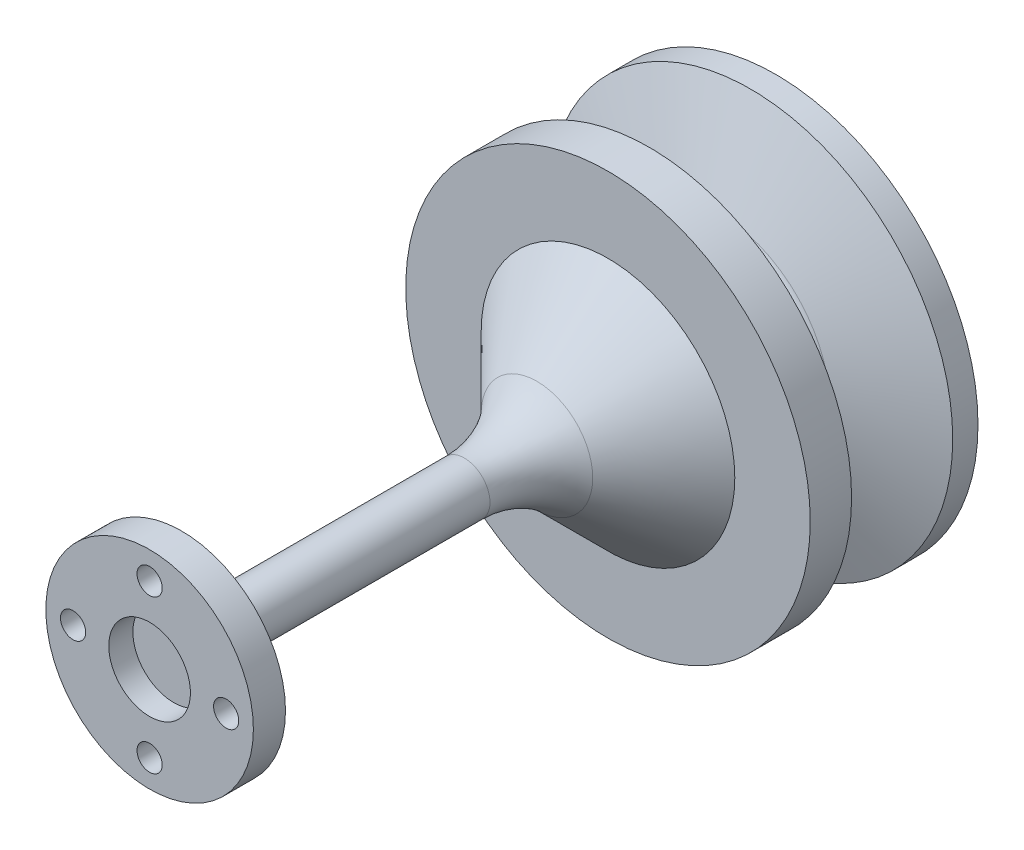
SolidWorks part; units mm, degrees
ref_plane "Plan de face" through (0, 0, 0) normal (0, 0, 1) x (1, 0, 0)
ref_plane "Plan de dessus" through (0, 0, 0) normal (0, 1, 0) x (1, 0, 0)
ref_plane "Plan de droite" through (0, 0, 0) normal (1, 0, 0) x (0, 0, -1)
sketch "Esquisse1" plane through (0, 0, 0) normal (0, 0, 1) x (1, 0, 0)
  circle A0 centre (0, 0) radius 20
  dimension "D1" = 40
extrude "Boss.-Extru.1" add sketch "Esquisse1" along normal mid plane 15
sketch "Esquisse4" plane through (0, 0, 0) normal (1, 0, 0) x (0, 0, -1)
  line L0 (-5, 20) -> (-1.3249, 10)
  line L1 (7.5, 20) -> (-7.5, 20) construction
  line L2 (-1.3249, 10) -> (1.3249, 10)
  line L3 (1.3249, 10) -> (5, 20)
  line L4 (5, 20) -> (-5, 20)
  line L5 (-15.7886, 0) -> (16.0217, 0) construction
  point P4 (0, 20)
  point P7 (0, 10)
  dimension "D1" = 10
  dimension "D2" = 10
  dimension "D3" = 3.6751
revolve "Enlèvement de matière-Révolution1" cut sketch "Esquisse4" angle 360 about L5
fillet "Congé1" radius 1.7 1 edges at (10, 0, -1.3249)
fillet "Congé3" radius 1.7 1 edges at (10, 0, 1.3249)
sketch "Esquisse5" plane through (0, 0, 7.5) normal (0, 0, 1) x (1, 0, 0)
  circle A0 centre (0, 0) radius 5
  dimension "D1" = 10
extrude "Enlèv. mat.-Extru.1" cut sketch "Esquisse5" against normal through all
sketch "Esquisse8" plane through (0, 0, 7.5) normal (0, 0, 1) x (1, 0, 0)
  circle A0 centre (0, 0) radius 2.54
  dimension "D1" = 5.08
extrude "Boss.-Extru.3" add sketch "Esquisse8" along normal blind 43.7388 separate body
sketch "Esquisse9" plane through (0, 0, 7.5) normal (0, 0, 1) x (1, 0, 0)
  circle A0 centre (0, 0) radius 20
extrude "Boss.-Extru.4" add sketch "Esquisse9" along normal blind 1.5875
sketch "Esquisse10" plane through (0, 0, 51.2388) normal (0, 0, 1) x (1, 0, 0)
  circle A0 centre (0, 0) radius 10.2616
  dimension "D1" = 20.5232
extrude "Boss.-Extru.5" add sketch "Esquisse10" along normal blind 3.175
sketch "Esquisse11" plane through (0, 0, 54.4138) normal (0, 0, 1) x (1, 0, 0)
  circle A0 centre (0, 7.5692) radius 1.2446
  dimension "D1" = 2.4892
  dimension "D2" = 7.5692
extrude "Enlèv. mat.-Extru.3" cut sketch "Esquisse11" against normal up to next
pattern_circular "Répétition circulaire2" count 4 over 360 about axis through (0, 0, 0) along (0, 0, 1) of "Enlèv. mat.-Extru.3"
sketch "Esquisse12" plane through (0, 0, 54.4138) normal (0, 0, 1) x (1, 0, 0)
  circle A0 centre (0, 0) radius 4.0386
  dimension "D1" = 8.0772
extrude "Enlèv. mat.-Extru.4" cut sketch "Esquisse12" against normal blind 2.3813
chamfer "Chamfer1" distance 10 angle 45 1 edges at (2.54, 0, 9.0875)
fillet "Fillet1" radius 10.16 1 edges at (2.54, 0, 19.0875)
